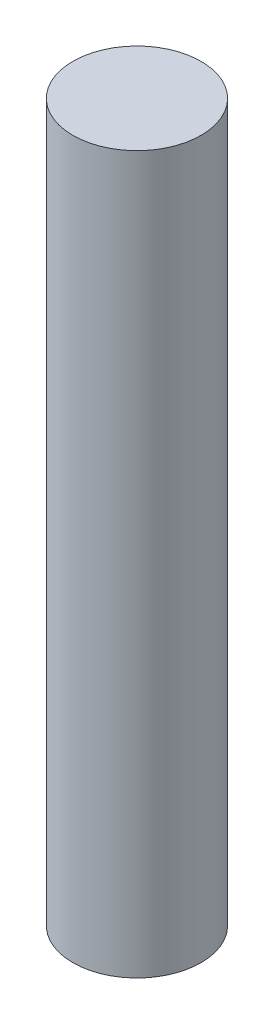
SolidWorks part; units mm, degrees
ref_plane "Front Plane" through (0, 0, 0) normal (0, 0, 1) x (1, 0, 0)
ref_plane "Top Plane" through (0, 0, 0) normal (0, 1, 0) x (1, 0, 0)
ref_plane "Right Plane" through (0, 0, 0) normal (1, 0, 0) x (0, 0, -1)
sketch "Sketch1" plane through (0, 0, 0) normal (0, 1, 0) x (1, 0, 0)
  circle A0 centre (0, 0) radius 5
extrude "Boss-Extrude1" add sketch "Sketch1" along normal blind 55.88
